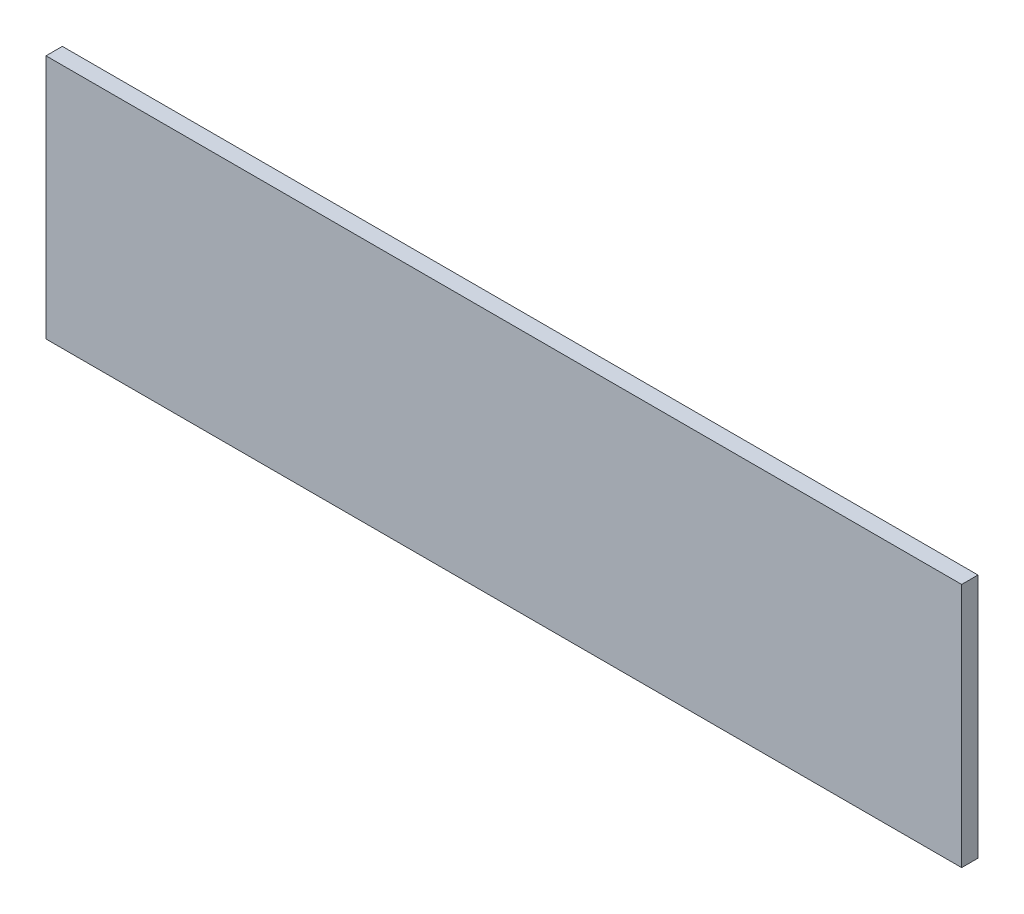
SolidWorks part; units mm, degrees
ref_plane "Plano frontal" through (0, 0, 0) normal (0, 0, 1) x (1, 0, 0)
ref_plane "Plano superior" through (0, 0, 0) normal (0, 1, 0) x (1, 0, 0)
ref_plane "Plano direito" through (0, 0, 0) normal (1, 0, 0) x (0, 0, -1)
sketch "Esboço1" plane through (0, 0, 0) normal (0, 0, 1) x (1, 0, 0)
  line L1 (58.5912, 23.6925) -> (2.5912, 23.6925)
  line L2 (58.5912, 23.6925) -> (58.5912, 38.6925)
  line L3 (58.5912, 38.6925) -> (2.5912, 38.6925)
  line L4 (2.5912, 23.6925) -> (2.5912, 38.6925)
  dimension "15" = 15
  dimension "D2" = 56
extrude "Ressalto-extrusão1" add sketch "Esboço1" along normal blind 1
